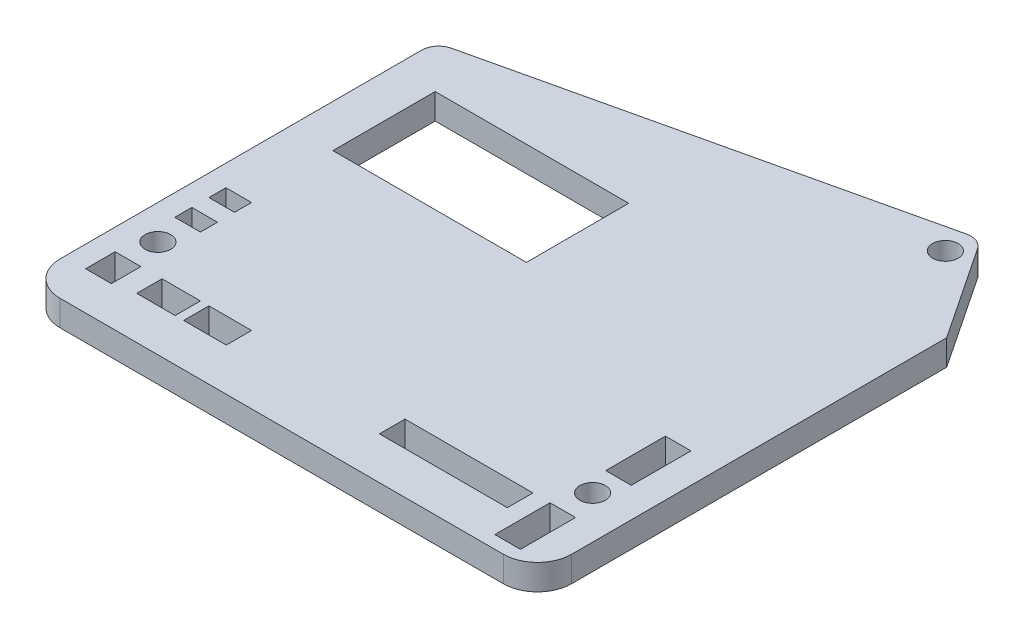
SolidWorks part; units mm, degrees
ref_plane "Alzado" through (0, 0, 0) normal (0, 0, 1) x (1, 0, 0)
ref_plane "Planta" through (0, 0, 0) normal (0, 1, 0) x (1, 0, 0)
ref_plane "Vista lateral" through (0, 0, 0) normal (1, 0, 0) x (0, 0, -1)
sketch "Croquis1" plane through (0, 0, 0) normal (0, 0, 1) x (1, 0, 0)
  line L0 (41808.5026, -312.7345) -> (41808.5026, -355.1434)
  line L1 (41812.5026, -308.7345) -> (41864.5026, -308.7345)
  line L2 (41868.5026, -312.7345) -> (41868.5026, -356.7345)
  line L3 (41868.5026, -356.7345) -> (41861.2695, -367.5842)
  line L4 (41859.1556, -368.4236) -> (41810.0529, -357.0922)
  line L5 (41862.0026, -316.6991) -> (41862.0026, -310.2345)
  line L6 (41811.0026, -313.2345) -> (41814.0227, -313.2345)
  line L7 (41811.0026, -313.2345) -> (41811.0026, -316.6956)
  line L8 (41811.0026, -316.6956) -> (41814.0227, -316.6956)
  line L9 (41814.0227, -313.2345) -> (41814.0227, -316.6956)
  line L10 (41816.5026, -313.7345) -> (41821.0026, -313.7345)
  line L11 (41816.5026, -313.7345) -> (41816.5026, -316.6991)
  line L13 (41821.0026, -313.7345) -> (41821.0026, -316.6991)
  line L14 (41822.0026, -313.7345) -> (41827.0026, -313.7345)
  line L15 (41822.0026, -313.7345) -> (41822.0026, -316.6991)
  line L17 (41827.0026, -313.7345) -> (41827.0026, -316.6991)
  line L18 (41845.0026, -313.6991) -> (41860.0026, -313.6991)
  line L19 (41845.0026, -313.6991) -> (41845.0026, -316.6991)
  line L21 (41860.0026, -313.6991) -> (41860.0026, -316.6991)
  line L22 (41862.0026, -310.2345) -> (41865.0026, -310.2345)
  line L24 (41862.0026, -316.6991) -> (41865.0026, -316.6991)
  line L26 (41862.0026, -323.2345) -> (41865.0026, -323.2345)
  line L28 (41862.0026, -330.2345) -> (41865.0026, -330.2345)
  line L30 (41811.0026, -323.6956) -> (41814.01, -323.6956)
  line L31 (41811.0026, -323.6956) -> (41811.0026, -325.6956)
  line L32 (41811.0026, -325.6956) -> (41814.01, -325.6956)
  line L33 (41814.01, -323.6956) -> (41814.01, -325.6956)
  line L34 (41811.0026, -327.6998) -> (41814.0044, -327.6998)
  line L35 (41811.0026, -327.6998) -> (41811.0026, -329.6956)
  line L36 (41811.0026, -329.6956) -> (41814.0044, -329.6956)
  line L37 (41814.0044, -327.6998) -> (41814.0044, -329.6956)
  line L38 (41813.5026, -339.7345) -> (41836.2026, -339.7345)
  line L39 (41813.5026, -339.7345) -> (41813.5026, -351.7345)
  line L40 (41813.5026, -351.7345) -> (41836.2026, -351.7345)
  line L41 (41836.2026, -339.7345) -> (41836.2026, -351.7345)
  line L42 (41865.0026, -330.2345) -> (41865.0026, -323.2345)
  line L44 (41865.0026, -316.6991) -> (41865.0026, -310.2345)
  line L45 (41862.0026, -330.2345) -> (41862.0026, -323.2345)
  line L48 (41860.0026, -316.6991) -> (41845.0026, -316.6991)
  line L49 (41821.0026, -316.6991) -> (41816.5026, -316.6991)
  line L50 (41827.0026, -316.6991) -> (41822.0026, -316.6991)
  arc A0 (41812.5026, -308.7345) -> (41808.5026, -312.7345) centre (41812.5026, -312.7345) ccw
  arc A1 (41868.5026, -312.7345) -> (41864.5026, -308.7345) centre (41864.5026, -312.7345) ccw
  arc A2 (41808.5026, -355.1434) -> (41810.0529, -357.0922) centre (41810.5026, -355.1434) ccw
  circle A3 centre (41859.6054, -365.4748) radius 1.5
  arc A4 (41859.1556, -368.4236) -> (41861.2695, -367.5842) centre (41859.6054, -366.4748) ccw
  circle A7 centre (41812.5178, -320.1956) radius 1.5
  circle A9 centre (41863.5026, -320.1991) radius 1.5
extrude "Saliente-Extruir1" add sketch "Croquis1" along normal blind 3
move or copy body "Sólido-Mover/Copiar1" bodies to move or copy 101 copy no rotation origin (0, -338.6046, 1.5) rotation axis (1, 0, 0) rotation angle 90
